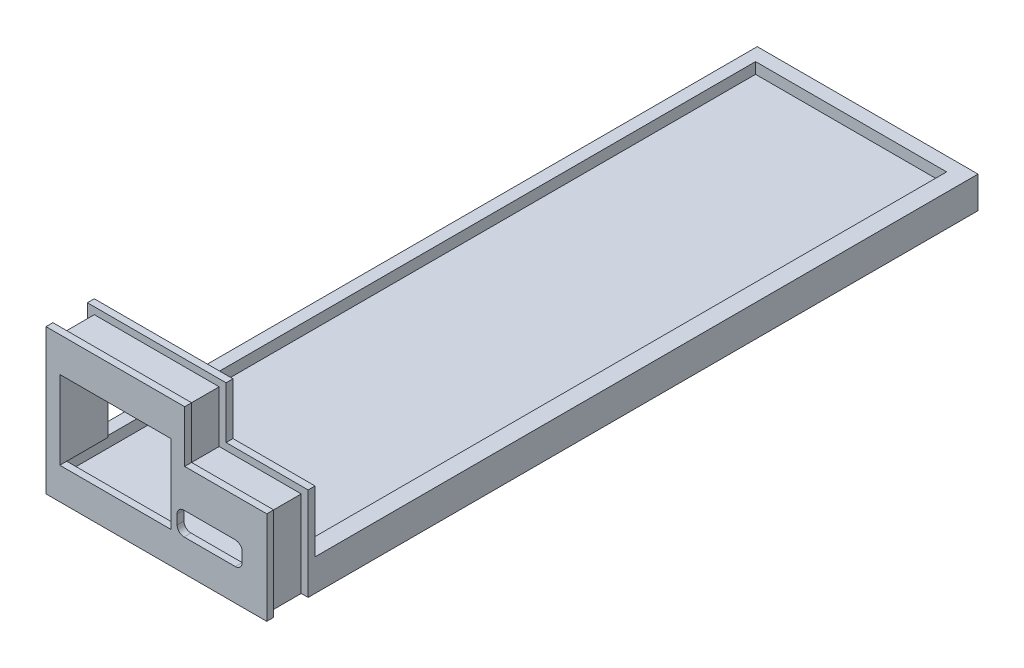
SolidWorks part; units mm, degrees
ref_plane "前视基准面" through (0, 0, 0) normal (0, 0, 1) x (1, 0, 0)
ref_plane "上视基准面" through (0, 0, 0) normal (0, 1, 0) x (1, 0, 0)
ref_plane "右视基准面" through (0, 0, 0) normal (1, 0, 0) x (0, 0, -1)
sketch "草图8" plane through (0, 0, 0) normal (0, 0, 1) x (1, 0, 0)
  line B0 (0.3449, 12.8) -> (0.3449, 1.6)
  line B1 (0.3449, 12.8) -> (16.0472, 12.8)
  line B2 (17.4431, 4.76) -> (26.3831, 4.76)
  line B3 (16.0472, 12.8) -> (16.0472, 1.6)
  line B4 (0, 1.6) -> (27.5001, 1.6)
  line B5 (0, 1.6) -> (0, 0)
  line B6 (0, 0) -> (27.5001, 0)
  line B7 (26.3831, 4.76) -> (26.3831, 1.6)
  line B8 (17.4431, 4.76) -> (17.4431, 1.6)
  line B9 (27.5001, 1.6) -> (27.5001, 0)
sketch_block_instance "left_board-1"
sketch_block "块1"
sketch "草图10" plane through (0, 0, 0) normal (0, 0, 1) x (1, 0, 0)
  line L0 (0.1449, 1.6) -> (0.1449, 13)
  line L1 (0.1449, 13) -> (16.2472, 13)
  line L2 (16.2472, 13) -> (16.2472, 4.96)
  line L3 (16.2472, 4.96) -> (26.5831, 4.96)
  line L4 (26.5831, 4.96) -> (26.5831, 1.6)
  line L5 (0.1449, 1.6) -> (26.5831, 1.6)
  line L6 (0, 1.6) -> (27.5001, 1.6) construction
  line L7 (0.3449, 12.8) -> (0.3449, 1.6) construction
  line L8 (16.0472, 12.8) -> (16.0472, 1.6) construction
  line L9 (0.3449, 12.8) -> (16.0472, 12.8) construction
  line L10 (17.4431, 4.76) -> (26.3831, 4.76) construction
  line L11 (26.3831, 4.76) -> (26.3831, 1.6) construction
  line L18 (-0.8551, -3) -> (29.1449, -3)
  line L19 (-0.8551, -3) -> (-0.8551, 17)
  line L20 (-0.8551, 17) -> (17.2472, 17)
  line L21 (17.2472, 17) -> (17.2472, 9.5)
  line L22 (17.2472, 9.5) -> (29.1449, 9.5)
  line L23 (29.1449, 9.5) -> (29.1449, -3)
  dimension "D1" = 0.2
  dimension "D2" = 0.2
  dimension "D3" = 0.2
  dimension "D4" = 0.2
  dimension "D5" = 0.2
  dimension "D6" = 30
  dimension "D7" = 20
  dimension "D8" = 12.5
  dimension "D9" = 4.6
  dimension "D10" = 1
  dimension "D11" = 1
extrude "凸台-拉伸2" add sketch "草图10" along normal blind 5
sketch "草图11" plane through (0, 0, 5) normal (0, 0, 1) x (1, 0, 0)
  line L15 (-1.8551, -3) -> (30.1449, -3)
  line L20 (30.1449, -3) -> (30.1449, 10.5)
  line L21 (30.1449, 10.5) -> (18.2472, 10.5)
  line L22 (18.2472, 10.5) -> (18.2472, 18)
  line L23 (-1.8551, 18) -> (-1.8551, -3)
  line L24 (18.2472, 18) -> (-1.8551, 18)
  line L25 (30.1449, -3) -> (30.1449, 10.5)
  line L26 (30.1449, 10.5) -> (18.2472, 10.5)
  line L27 (18.2472, 10.5) -> (18.2472, 18)
  line L28 (-1.8551, 18) -> (-1.8551, -3)
  line L29 (18.2472, 18) -> (-1.8551, 18)
  dimension "D1" = 1
extrude "凸台-拉伸3" add sketch "草图11" along normal blind 1
sketch "草图12" plane through (0, 0, 0) normal (0, 0, -1) x (-1, 0, 0)
  line L56 (0.8551, -3) -> (1.8551, -3)
  line L57 (-29.1449, -3) -> (0.8551, -3)
  line L58 (-30.1449, -3) -> (-29.1449, -3)
  line L59 (1.8551, -3) -> (1.8551, 18)
  line L60 (1.8551, 18) -> (-18.2472, 18)
  line L61 (-18.2472, 18) -> (-18.2472, 10.5)
  line L62 (-18.2472, 10.5) -> (-30.1449, 10.5)
  line L63 (-30.1449, 10.5) -> (-30.1449, -3)
  line L64 (0.8551, -3) -> (1.8551, -3)
  line L65 (-29.1449, -3) -> (0.8551, -3)
  line L66 (-30.1449, -3) -> (-29.1449, -3)
  line L67 (1.8551, -3) -> (1.8551, 18)
  line L68 (1.8551, 18) -> (-18.2472, 18)
  line L69 (-18.2472, 18) -> (-18.2472, 10.5)
  line L70 (-18.2472, 10.5) -> (-30.1449, 10.5)
  line L71 (-30.1449, 10.5) -> (-30.1449, -3)
  dimension "D1" = 0
extrude "凸台-拉伸4" add sketch "草图12" along normal blind 1
sketch "草图13" plane through (0, 0, 6) normal (0, 0, 1) x (1, 0, 0)
  line L28 (16.2472, 4.96) -> (16.2472, 13)
  line L29 (26.5831, 4.96) -> (16.2472, 4.96)
  line L30 (26.5831, 1.6) -> (26.5831, 4.96)
  line L31 (0.1449, 1.6) -> (26.5831, 1.6)
  line L32 (0.1449, 13) -> (0.1449, 1.6)
  line L33 (16.2472, 13) -> (0.1449, 13)
  line L34 (16.2472, 4.96) -> (16.2472, 13)
  line L35 (26.5831, 4.96) -> (16.2472, 4.96)
  line L36 (26.5831, 1.6) -> (26.5831, 4.96)
  line L37 (0.1449, 1.6) -> (26.5831, 1.6)
  line L38 (0.1449, 13) -> (0.1449, 1.6)
  line L39 (16.2472, 13) -> (0.1449, 13)
  dimension "D1" = 0
extrude "切除-拉伸1" cut sketch "草图13" against normal through all
sketch "草图14" plane through (0, 0, -1) normal (0, 0, -1) x (-1, 0, 0)
  line L0 (0, 0) -> (-27.5001, 0) construction
  line L1 (0.1, 0) -> (-27.6001, 0)
  line L2 (0.1, 0) -> (0.1, 1.6)
  line L3 (0.1, 1.6) -> (-27.6001, 1.6)
  line L4 (-27.6001, 0) -> (-27.6001, 1.6)
  line L5 (-27.5001, 1.6) -> (-27.5001, 0) construction
  line L6 (0, 1.6) -> (0, 0) construction
  line L7 (0, 1.6) -> (-27.5001, 1.6) construction
  dimension "D1" = 0
  dimension "D2" = 0.1
  dimension "D3" = 0.1
  dimension "D4" = 0
extrude "切除-拉伸2" cut sketch "草图14" against normal blind 6
sketch "草图15" plane through (0, 0, -1) normal (0, 0, -1) x (-1, 0, 0)
  line L6 (-30.1449, -3) -> (1.8551, -3)
  line L7 (1.8551, -3) -> (1.8551, 1.6)
  line L8 (1.8551, -3) -> (1.8551, 18) construction
  line L9 (1.8551, 1.6) -> (0.1, 1.6)
  line L10 (-0.1449, 1.6) -> (-26.5831, 1.6) construction
  line L11 (0.1, 0) -> (0.1, 1.6) construction
  line L12 (0.1, 1.6) -> (0.1, 0)
  line L13 (0.1, 0) -> (-27.6001, 0)
  line L14 (-27.6001, 0) -> (-27.6001, 1.6)
  line L15 (-27.6001, 1.6) -> (-30.1449, 1.6)
  line L16 (-30.1449, 10.5) -> (-30.1449, -3) construction
  line L17 (-30.1449, 1.6) -> (-30.1449, -3)
extrude "凸台-拉伸7" add sketch "草图15" along normal blind 94.1
sketch "草图16" plane through (0, 0, -95.1) normal (0, 0, -1) x (-1, 0, 0)
  line L1 (-30.1449, -3) -> (1.8551, -3)
  line L2 (-30.1449, -3) -> (-30.1449, 1.6)
  line L3 (-30.1449, 1.6) -> (1.8551, 1.6)
  line L4 (1.8551, -3) -> (1.8551, 1.6)
extrude "凸台-拉伸8" add sketch "草图16" along normal blind 2
sketch "草图18" plane through (0, 1.6, 0) normal (0, 1, 0) x (1, 0, 0)
  line L0 (18.2472, -5) -> (-1.8551, -5) construction
  line L1 (16.2472, -6) -> (17.1472, -6)
  line L2 (16.2472, -6) -> (16.2472, -5)
  line L3 (16.2472, -5) -> (17.1472, -5)
  line L4 (17.1472, -6) -> (17.1472, -5)
  line L6 (17.2472, -5) -> (17.2472, 0) construction
  dimension "D1" = 0.1
extrude "凸台-拉伸10" add sketch "草图18" along direction (0, -1, 0) on the side of the normal up to next (3.36 mm away)
fillet "圆角2" radius 1 4 edges at (26.5831, 1.6, 5.5) (26.5831, 4.96, 2.5) (17.1472, 1.6, 5.5) (17.1472, 4.96, 5.5)
